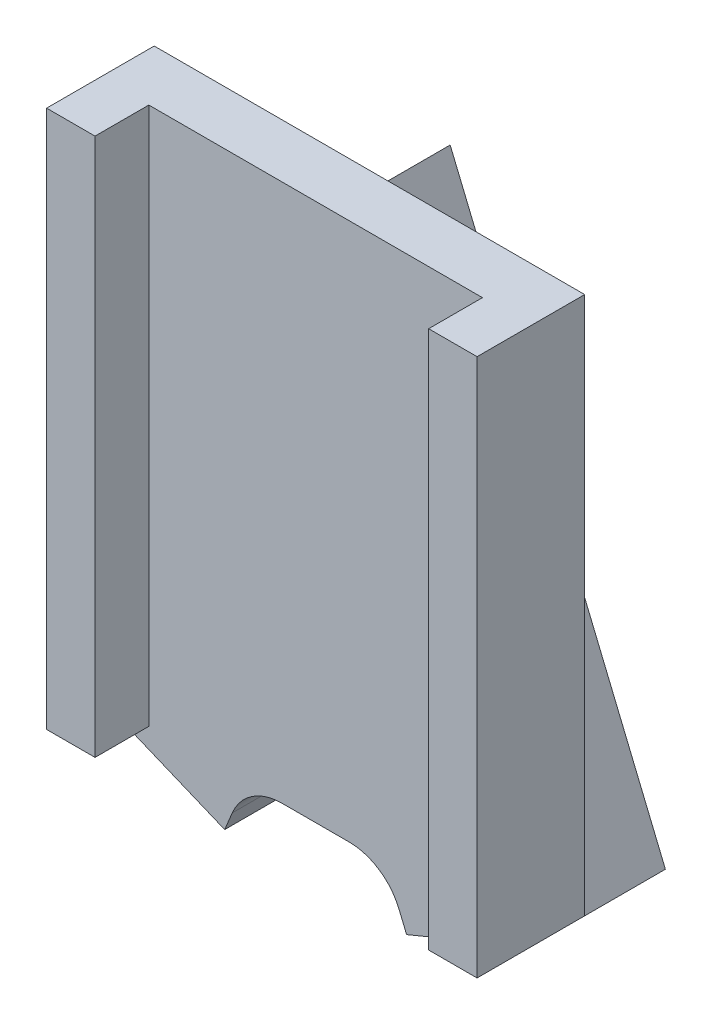
SolidWorks part; units mm, degrees
ref_plane "Ebene vorne" through (0, 0, 0) normal (0, 0, 1) x (1, 0, 0)
ref_plane "Ebene oben" through (0, 0, 0) normal (0, 1, 0) x (1, 0, 0)
ref_plane "Ebene rechts" through (0, 0, 0) normal (1, 0, 0) x (0, 0, -1)
sketch "Sketch1" plane through (0, 0, 0) normal (0, 0, 1) x (1, 0, 0)
  line L1 (0, 0) -> (8, 0)
  line L2 (0, 0) -> (0, -10)
  line L3 (0, -10) -> (8, -10)
  line L4 (8, 0) -> (8, -10)
extrude "Boss-Extrude1" add sketch "Sketch1" along normal blind 2
sketch "Sketch2" plane through (0, 0, 2) normal (0, 0, 1) x (1, 0, 0)
  line L0 (8, 0) -> (0, 0) construction
  line L1 (0.9, 0) -> (7.1, 0)
  line L2 (0.9, 0) -> (0.9, -10)
  line L3 (0.9, -10) -> (7.1, -10)
  line L4 (7.1, 0) -> (7.1, -10)
  line L5 (0, -10) -> (8, -10) construction
  line L6 (0, 0) -> (0, -10) construction
  line L7 (8, -10) -> (8, 0) construction
  dimension "D1" = 0.9
  dimension "D2" = 0.9
  dimension "D3" = 6.2
extrude "Cut-Extrude1" cut sketch "Sketch2" against normal blind 1
sketch "Sketch3" plane through (0, 0, 0) normal (0, 0, -1) x (-1, 0, 0)
  line L0 (-8, -10) -> (-4, -0.3431)
  line L1 (-8, -10) -> (-5.6903, -10.9567)
  line L4 (-4, 0) -> (-4, -10) construction
  line L5 (-8, 0) -> (0, 0) construction
  line L6 (0, -10) -> (-8, -10) construction
  line L7 (-8, -5) -> (0, -5) construction
  line L8 (-8, -10) -> (-8, 0) construction
  line L9 (0, 0) -> (0, -10) construction
  line L10 (0, -10) -> (-4, -0.3431)
  line L11 (-4, -6.876) -> (-5.6903, -10.9567)
  line L12 (0, -10) -> (-2.3097, -10.9567)
  line L13 (-2.3097, -10.9567) -> (-4, -6.876)
  dimension "D1" = 2.5
  dimension "D2" = 2.5
  dimension "D3" = 45
extrude "Boss-Extrude2" add sketch "Sketch3" along normal blind 1.5 and the other way blind 1
hole_wizard "M1 Clearance Hole2" positions "Sketch5" profile "Sketch4" hole size "M1" standard "DIN"
sketch "Sketch5" plane through (-3.5355, -8.5355, 0) normal (-0.3827, -0.9239, 0) x (-0.9239, 0.3827, 0)
  line L0 (-5.0768, 1.5) -> (-5.0768, -1) construction
  line L1 (-6.3268, 1.5) -> (-3.8268, 1.5) construction
  line L2 (-6.3268, -1) -> (-3.8268, -1) construction
  line L4 (-6.3268, 0.25) -> (-3.8268, 0.25) construction
  line L5 (-6.3268, -1) -> (-6.3268, 1.5) construction
  line L6 (-3.8268, 0) -> (-3.8268, 1.5) construction
  point P0 (-5.116, 0.25)
sketch "Sketch4" plane through (1.191, -10.4933, -0.25) normal (0, 0, 1) x (0.9239, -0.3827, 0)
  line L0 (0, 0) -> (0, 5.3605)
  line L1 (0, 5.3605) -> (0.6, 5)
  line L2 (0.6, 5) -> (0.6, 0)
  line L5 (0.6, 0) -> (0, 0)
  line L10 (0, 5.3605) -> (-0.6, 5) construction
  line L11 (0, -6.35) -> (0, 107.95) construction
  dimension "Hole Dia." = 1.2
  dimension "Hole Depth" = 5
  dimension "Drill Angle" = 118
hole_wizard "M1 Clearance Hole1" positions "Sketch6" profile "Sketch7" hole size "M1" standard "DIN"
sketch "Sketch6" plane through (4.7071, -11.364, 0) normal (0.3827, -0.9239, 0) x (-0.9239, -0.3827, 0)
  line L0 (-1.0642, 0.25) -> (-3.5642, 0.25) construction
  line L1 (-1.0642, -1) -> (-1.0642, 1.5) construction
  line L2 (-3.5642, 0) -> (-3.5642, 1.5) construction
  line L4 (-2.3142, -1) -> (-2.3142, 1.5) construction
  line L5 (-3.5642, -1) -> (-1.0642, -1) construction
  line L6 (-3.5642, 1.5) -> (-1.0642, 1.5) construction
  point P0 (-2.3142, 0.25)
sketch "Sketch7" plane through (6.8452, -10.4784, -0.25) normal (0, 0, 1) x (0.9239, 0.3827, 0)
  line L0 (0, 0) -> (0, 5.3004)
  line L1 (0, 5.3004) -> (0.5, 5)
  line L2 (0.5, 5) -> (0.5, 0)
  line L5 (0.5, 0) -> (0, 0)
  line L10 (0, 5.3004) -> (-0.5, 5) construction
  line L11 (0, -6.35) -> (0, 107.95) construction
  dimension "Hole Dia." = 1
  dimension "Hole Depth" = 5
  dimension "Drill Angle" = 118
sketch "Sketch8" plane through (0, 0, -1.5) normal (0, 0, -1) x (-1, 0, 0)
  circle A0 centre (-4, -7.3) radius 0.4
extrude "Cut-Extrude2" cut sketch "Sketch8" against normal blind 1.5
fillet "Fillet2" radius 1 2 edges at (2.706, -10, 0.5) (5.294, -10, 0.5)
